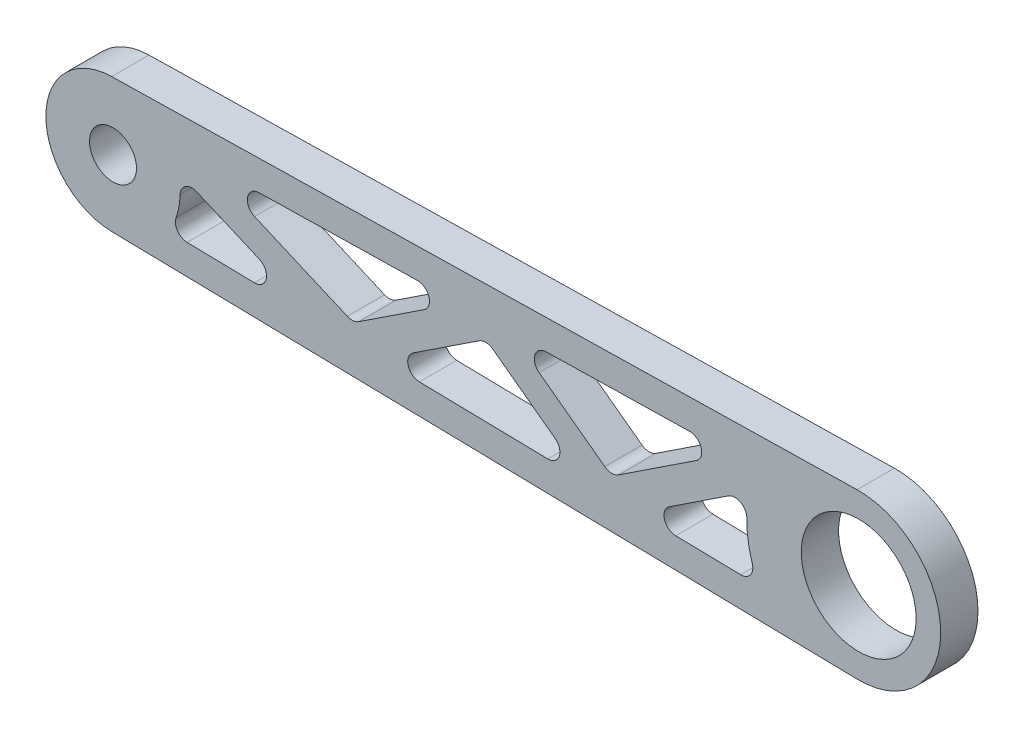
SolidWorks part; units mm, degrees
material "黑板"
ref_plane "前视基准面" through (0, 0, 0) normal (0, 0, 1) x (1, 0, 0)
ref_plane "上视基准面" through (0, 0, 0) normal (0, 1, 0) x (1, 0, 0)
ref_plane "右视基准面" through (0, 0, 0) normal (1, 0, 0) x (0, 0, -1)
sketch "草图1" plane through (0, 0, 0) normal (0, 0, 1) x (1, 0, 0)
  line L0 (0, 0) -> (100, 0) construction
  line L1 (-0.18, -8.9982) -> (99.78, -10.9978)
  line L2 (-0.18, 8.9982) -> (99.78, 10.9978)
  arc A0 (-0.18, 8.9982) -> (-0.18, -8.9982) centre (0, 0) ccw
  arc A1 (99.78, -10.9978) -> (99.78, 10.9978) centre (100, 0) ccw
  arc A2 (-0.18, -8.9982) -> (9, 0) centre (0, 0) ccw construction
  arc A3 (9, 0) -> (-0.18, 8.9982) centre (0, 0) ccw construction
  arc A4 (99.78, 10.9978) -> (89, 0) centre (100, 0) ccw construction
  arc A5 (89, 0) -> (99.78, -10.9978) centre (100, 0) ccw construction
  dimension "D1" = 100
  dimension "D2" = 18
  dimension "D3" = 22
extrude "凸台-拉伸1" add sketch "草图1" along normal blind 5
sketch "草图2" plane through (0, 0, 5) normal (0, 0, 1) x (1, 0, 0)
  circle A0 centre (0, 0) radius 3.15
  dimension "D1" = 6.3
extrude "切除-拉伸1" cut sketch "草图2" against normal through all
sketch "草图3" plane through (0, 0, 5) normal (0, 0, 1) x (1, 0, 0)
  circle A0 centre (100, 0) radius 7.7
  arc A1 (99.78, -10.9978) -> (99.78, 10.9978) centre (100, 0) ccw construction
  dimension "D1" = 15.4
extrude "切除-拉伸2" cut sketch "草图3" against normal through all
sketch "草图4" plane through (0, 0, 5) normal (0, 0, 1) x (1, 0, 0)
  line L0 (7.3818, 5.1487) -> (86.5962, 6.7333)
  line L1 (86.5962, -6.7333) -> (7.3818, -5.1487)
  line L2 (99.78, 10.9978) -> (-0.18, 8.9982) construction
  line L3 (-0.18, -8.9982) -> (99.78, -10.9978) construction
  arc A0 (7.3818, -5.1487) -> (7.3818, 5.1487) centre (0, 0) ccw
  arc A1 (86.5962, 6.7333) -> (86.5962, -6.7333) centre (100, 0) ccw
  arc A2 (-0.18, 8.9982) -> (-0.18, -8.9982) centre (0, 0) ccw construction
  arc A3 (86.5962, -6.7333) -> (86.5962, 6.7333) centre (100, 0) ccw construction
  arc A4 (7.3818, 5.1487) -> (7.3818, -5.1487) centre (0, 0) ccw construction
  dimension "D1" = 30
  dimension "D2" = 4
  dimension "D3" = 4
extrude "切除-拉伸3" cut sketch "草图4" against normal through all
sketch "草图5" plane through (0, 0, 5) normal (0, 0, 1) x (1, 0, 0)
  line L0 (7.3818, 5.1487) -> (32.417, -5.6495)
  line L1 (7.3818, -5.1487) -> (86.5962, -6.7333) construction
  line L2 (32.417, -5.6495) -> (50.0961, 6.0031)
  line L3 (86.5962, 6.7333) -> (7.3818, 5.1487) construction
  line L4 (50.0961, 6.0031) -> (66.7825, -6.3369)
  line L5 (66.7825, -6.3369) -> (86.5962, 6.7333)
extrude "拉伸-薄壁1" add sketch "草图5" against normal through all thin thin type mid plane wall 4
fillet "圆角1" radius 1.6 15 edges at (82.8504, 6.6583, 2.5) (66.8479, -3.8978, 2.5) (53.3711, 6.0686, 2.5) (46.3481, 5.9281, 2.5) (12.2079, 5.2452, 2.5) (27.1215, -5.5435, 2.5) (7.3818, -5.1487, 2.5) (50.0302, 3.5643, 2.5) (63.3253, -6.2678, 2.5) (35.9441, -5.72, 2.5) (85.4307, 3.5685, 2.5) (86.5962, -6.7333, 2.5) (70.3077, -6.4074, 2.5) (32.2178, -3.3854, 2.5) (8.6699, 2.415, 2.5)
